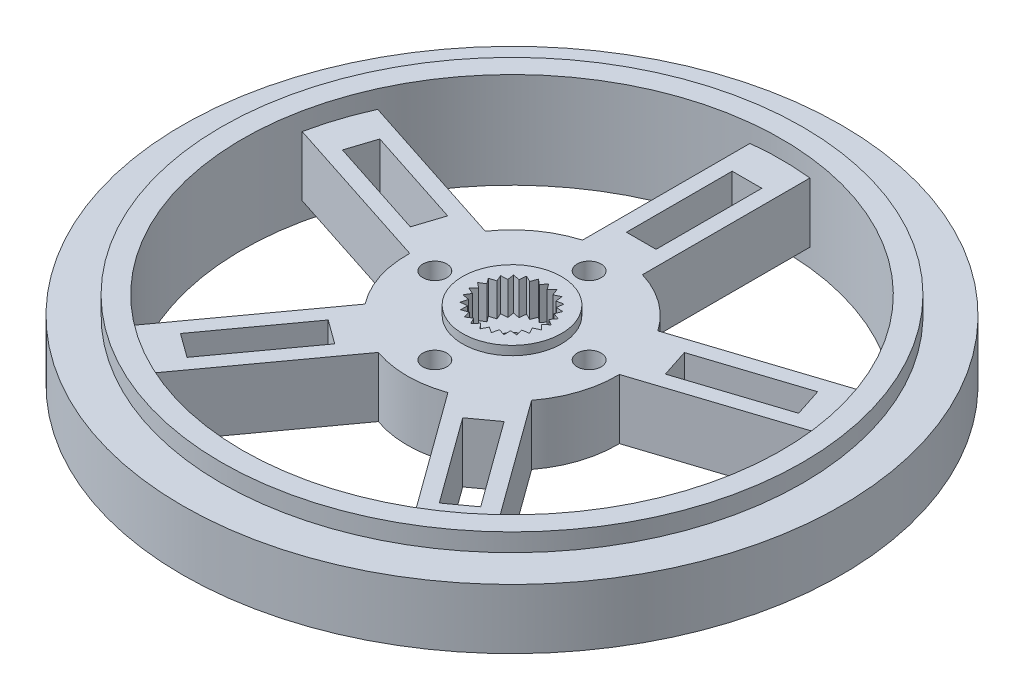
SolidWorks part; units mm, degrees
ref_plane "Front Plane" through (0, 0, 0) normal (0, 0, 1) x (1, 0, 0)
ref_plane "Top Plane" through (0, 0, 0) normal (0, 1, 0) x (1, 0, 0)
ref_plane "Right Plane" through (0, 0, 0) normal (1, 0, 0) x (0, 0, -1)
sketch "Sketch2" plane through (0, 0, 0) normal (0, 1, 0) x (1, 0, 0)
  circle A0 centre (0, 0) radius 27.94
  dimension "D1" = 55.88
extrude "Boss-Extrude1" add sketch "Sketch2" along normal blind 5.08
sketch "Sketch3" plane through (0, 5.08, 0) normal (0, 1, 0) x (1, 0, 0)
  circle A0 centre (0, 0) radius 22.86
  dimension "D1" = 45.72
extrude "Cut-Extrude1" cut sketch "Sketch3" against normal through all
sketch "Sketch4" plane through (0, 5.08, 0) normal (0, 1, 0) x (1, 0, 0)
  line L0 (0, 24.638) -> (0, 22.86) construction
  circle A0 centre (0, 0) radius 24.638
  circle A1 centre (0, 0) radius 22.86 construction
  circle A2 centre (0, 0) radius 22.86
  dimension "D1" = 1.778
extrude "Boss-Extrude2" add sketch "Sketch4" along normal blind 1.524 and the other way blind 6.604
sketch "Sketch5" plane through (0, 5.08, 0) normal (0, 1, 0) x (1, 0, 0)
  line L0 (5.2782, 4.3857) -> (22.5224, 9.9887)
  line L1 (2.54, 6.3751) -> (-2.54, 6.3751)
  line L2 (2.54, 6.3751) -> (2.54, 24.5067)
  line L3 (2.54, 24.5067) -> (-2.54, 24.5067)
  line L4 (-2.54, 6.3751) -> (-2.54, 24.5067)
  line L5 (2.54, 6.3751) -> (-2.54, 24.5067) construction
  line L6 (2.54, 24.5067) -> (-2.54, 6.3751) construction
  line L7 (6.848, -0.4457) -> (5.2782, 4.3857)
  line L8 (6.848, -0.4457) -> (24.0922, 5.1573)
  line L9 (24.0922, 5.1573) -> (22.5224, 9.9887)
  line L10 (5.8021, -3.6646) -> (16.4596, -18.3334)
  line L11 (1.6923, -6.6506) -> (5.8021, -3.6646)
  line L12 (1.6923, -6.6506) -> (12.3498, -21.3193)
  line L13 (12.3498, -21.3193) -> (16.4596, -18.3334)
  line L14 (-1.6923, -6.6506) -> (-12.3498, -21.3193)
  line L15 (-5.8021, -3.6646) -> (-1.6923, -6.6506)
  line L16 (-5.8021, -3.6646) -> (-16.4596, -18.3334)
  line L17 (-16.4596, -18.3334) -> (-12.3498, -21.3193)
  line L18 (-6.848, -0.4457) -> (-24.0922, 5.1573)
  line L19 (-5.2782, 4.3857) -> (-6.848, -0.4457)
  line L20 (-5.2782, 4.3857) -> (-22.5224, 9.9887)
  line L21 (-22.5224, 9.9887) -> (-24.0922, 5.1573)
  line L22 (10.8102, 2.192) -> (10.0341, 4.5808)
  line L23 (1.2559, 10.9585) -> (-1.2559, 10.9585)
  line L24 (1.2559, 10.9585) -> (1.2559, 19.9234)
  line L25 (1.2559, 19.9234) -> (-1.2559, 19.9234)
  line L26 (-1.2559, 10.9585) -> (-1.2559, 19.9234)
  line L27 (1.2559, 10.9585) -> (-1.2559, 19.9234) construction
  line L28 (1.2559, 19.9234) -> (-1.2559, 10.9585) construction
  line L29 (10.0341, 4.5808) -> (18.5602, 7.3511)
  line L30 (10.8102, 2.192) -> (19.3363, 4.9623)
  line L31 (19.3363, 4.9623) -> (18.5602, 7.3511)
  line L32 (5.4252, -9.6038) -> (7.4573, -8.1274)
  line L33 (7.4573, -8.1274) -> (12.7267, -15.3802)
  line L34 (5.4252, -9.6038) -> (10.6946, -16.8565)
  line L35 (10.6946, -16.8565) -> (12.7267, -15.3802)
  line L36 (-7.4573, -8.1274) -> (-5.4252, -9.6038)
  line L37 (-5.4252, -9.6038) -> (-10.6946, -16.8565)
  line L38 (-7.4573, -8.1274) -> (-12.7267, -15.3802)
  line L39 (-12.7267, -15.3802) -> (-10.6946, -16.8565)
  line L40 (-10.0341, 4.5808) -> (-10.8102, 2.192)
  line L41 (-10.8102, 2.192) -> (-19.3363, 4.9623)
  line L42 (-10.0341, 4.5808) -> (-18.5602, 7.3511)
  line L43 (-18.5602, 7.3511) -> (-19.3363, 4.9623)
  circle A0 centre (0, 0) radius 8.89
  circle A1 centre (0, 0) radius 24.638 construction
  point P3 (0, 15.4409)
  point P10 (0, 15.4409)
  point P29 (0, 0)
  point P50 (0, 0)
  dimension "D1" = 17.78
  dimension "D2" = 5.08
  dimension "D3" = 5
  dimension "D4" = 5
extrude "Boss-Extrude4" add sketch "Sketch5" against normal blind 5.08 contours A0 L16 L17 L14 | L16 A0 L14 L15 | L10 A0 L8 L7 L0 L2 L1 L4 L20 L19 L18 L16 L15 L14 L12 L11 | L20 A0 L18 L19 | A0 L20 L21 L18 | L12 A0 L10 L11 | A0 L12 L13 L10 | A0 L8 L9 L0 | L8 A0 L0 L7 | L2 A0 L4 L1 | A0 L2 L3 L4
sketch "Sketch6" plane through (0, 5.08, 0) normal (0, 1, 0) x (1, 0, 0)
  circle A0 centre (0, 0) radius 4.191
  circle A1 centre (0, 0) radius 2.667
  dimension "D1" = 8.382
  dimension "D2" = 5.334
extrude "Boss-Extrude5" add sketch "Sketch6" along normal blind 0.762
sketch "Sketch8" plane through (0, 5.842, 0) normal (0, 1, 0) x (1, 0, 0)
  circle A0 centre (0, 0) radius 2.667
  circle A1 centre (0, 0) radius 2.667 construction
extrude "Cut-Extrude2" cut sketch "Sketch8" against normal blind 2.794
sketch "Sketch9" plane through (0, 5.842, 0) normal (0, 1, 0) x (1, 0, 0)
  line L0 (0, 3.1251) -> (-0.3343, 2.646)
  line L1 (0, 3.1251) -> (0.3343, 2.646)
  line L2 (-0.3343, 2.646) -> (0, 0) construction
  line L3 (0, 0) -> (0.3343, 2.646) construction
  line L4 (0.7772, 3.0269) -> (0.3343, 2.646)
  line L5 (0.7772, 3.0269) -> (0.9818, 2.4797)
  line L6 (1.5055, 2.7385) -> (0.9818, 2.4797)
  line L7 (1.5055, 2.7385) -> (1.5676, 2.1576)
  line L8 (2.1393, 2.2781) -> (1.5676, 2.1576)
  line L9 (2.1393, 2.2781) -> (2.055, 1.7)
  line L10 (2.6386, 1.6745) -> (2.055, 1.7)
  line L11 (2.6386, 1.6745) -> (2.4132, 1.1356)
  line L12 (2.9721, 0.9657) -> (2.4132, 1.1356)
  line L13 (2.9721, 0.9657) -> (2.6198, 0.4997)
  line L14 (3.1189, 0.1962) -> (2.6198, 0.4997)
  line L15 (3.1189, 0.1962) -> (2.6617, -0.1675)
  line L16 (3.0697, -0.5856) -> (2.6617, -0.1675)
  line L17 (3.0697, -0.5856) -> (2.5365, -0.8241)
  line L18 (2.8277, -1.3306) -> (2.5365, -0.8241)
  line L19 (2.8277, -1.3306) -> (2.2518, -1.4291)
  line L20 (2.4079, -1.992) -> (2.2518, -1.4291)
  line L21 (2.4079, -1.992) -> (1.8257, -1.9442)
  line L22 (1.8369, -2.5283) -> (1.8257, -1.9442)
  line L23 (1.8369, -2.5283) -> (1.2848, -2.3371)
  line L24 (1.1504, -2.9056) -> (1.2848, -2.3371)
  line L25 (1.1504, -2.9056) -> (0.6633, -2.5832)
  line L26 (0.3917, -3.1004) -> (0.6633, -2.5832)
  line L27 (0.3917, -3.1004) -> (0, -2.667)
  line L28 (-0.3917, -3.1004) -> (0, -2.667)
  line L29 (-0.3917, -3.1004) -> (-0.6633, -2.5832)
  line L30 (-1.1504, -2.9056) -> (-0.6633, -2.5832)
  line L31 (-1.1504, -2.9056) -> (-1.2848, -2.3371)
  line L32 (-1.8369, -2.5283) -> (-1.2848, -2.3371)
  line L33 (-1.8369, -2.5283) -> (-1.8257, -1.9442)
  line L34 (-2.4079, -1.992) -> (-1.8257, -1.9442)
  line L35 (-2.4079, -1.992) -> (-2.2518, -1.4291)
  line L36 (-2.8277, -1.3306) -> (-2.2518, -1.4291)
  line L37 (-2.8277, -1.3306) -> (-2.5365, -0.8241)
  line L38 (-3.0697, -0.5856) -> (-2.5365, -0.8241)
  line L39 (-3.0697, -0.5856) -> (-2.6617, -0.1675)
  line L40 (-3.1189, 0.1962) -> (-2.6617, -0.1675)
  line L41 (-3.1189, 0.1962) -> (-2.6198, 0.4997)
  line L42 (-2.9721, 0.9657) -> (-2.6198, 0.4997)
  line L43 (-2.9721, 0.9657) -> (-2.4132, 1.1356)
  line L44 (-2.6386, 1.6745) -> (-2.4132, 1.1356)
  line L45 (-2.6386, 1.6745) -> (-2.055, 1.7)
  line L46 (-2.1393, 2.2781) -> (-2.055, 1.7)
  line L47 (-2.1393, 2.2781) -> (-1.5676, 2.1576)
  line L48 (-1.5055, 2.7385) -> (-1.5676, 2.1576)
  line L49 (-1.5055, 2.7385) -> (-0.9818, 2.4797)
  line L50 (-0.7772, 3.0269) -> (-0.9818, 2.4797)
  line L51 (-0.7772, 3.0269) -> (-0.3343, 2.646)
  line L52 (0, 3.1251) -> (0, 2.667) construction
  circle A0 centre (0, 0) radius 2.667 construction
  circle A1 centre (0, 0) radius 2.667 construction
  point P84 (0, 0)
  dimension "D1" = 0.5842
  dimension "D2" = 14.4
  dimension "D3" = 25
extrude "Cut-Extrude3" cut sketch "Sketch9" against normal blind 2.794
sketch "Sketch10" plane through (0, 3.048, 0) normal (0, 1, 0) x (1, 0, 0)
  circle A0 centre (0, 0) radius 1.1176
  dimension "D1" = 2.2352
extrude "Cut-Extrude4" cut sketch "Sketch10" against normal through all
sketch "Sketch11" plane through (0, 5.08, 0) normal (0, 1, 0) x (1, 0, 0)
  line L0 (0, 6.5405) -> (0, 4.191) construction
  line L1 (0, 6.5405) -> (0, 8.89) construction
  circle A0 centre (0, 6.5405) radius 1.016
  circle A1 centre (0, 0) radius 4.191 construction
  circle A2 centre (0, 0) radius 8.89 construction
  arc A3 (-2.54, 8.5194) -> (-7.3175, 5.0483) centre (0, 0) ccw construction
  circle A4 centre (6.5405, 0) radius 1.016
  circle A5 centre (0, -6.5405) radius 1.016
  circle A6 centre (-6.5405, 0) radius 1.016
  point P22 (0, 0)
  dimension "D1" = 2.032
  dimension "D2" = 4
extrude "Cut-Extrude5" cut sketch "Sketch11" against normal through all
